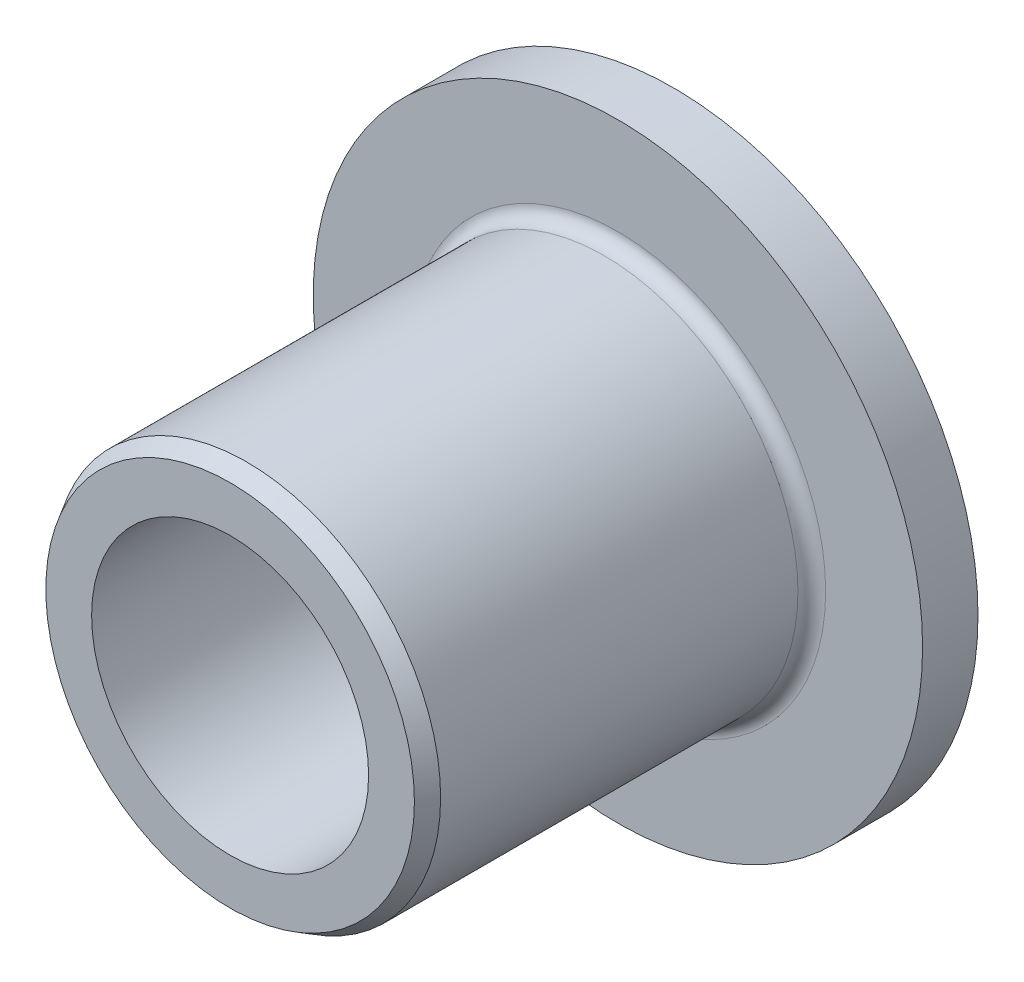
SolidWorks part; units mm, degrees
material "Igus T500"
ref_plane "Front Plane" through (0, 0, 0) normal (0, 0, 1) x (1, 0, 0)
ref_plane "Top Plane" through (0, 0, 0) normal (0, 1, 0) x (1, 0, 0)
ref_plane "Right Plane" through (0, 0, 0) normal (1, 0, 0) x (0, 0, -1)
ref_plane "Plane1" through (0, 0, 0) normal (0, 1, 0) x (-1, 0, 0)
sketch "Sketch1" plane through (0, 0, 0) normal (0, 1, 0) x (-1, 0, 0)
  line L0 (-3.5, 1) -> (-5.5, 1)
  line L1 (-5.5, 0) -> (-2.5, 0)
  line L2 (-2.5, 0) -> (-2.5, 8)
  line L3 (-3.3268, 8) -> (-3.5, 7.7)
  line L4 (-3.5, 7.7) -> (-3.5, 1)
  line L5 (0, 0) -> (0, 9.5) construction
  line L6 (-2.5, 8) -> (-3.3268, 8)
  line L8 (-5.5, 1) -> (-5.5, 0)
  dimension "D8" = 0.3
  dimension "d3" = 11
  dimension "b2" = 1
  dimension "D7" = 30
  dimension "b1" = 8
  dimension "d1" = 5
  dimension "d2" = 7
revolve "Revolve1" add sketch "Sketch1" angle 360 about L5
fillet "Fillet1" radius 0.25 1 edges at (3.5, 0, 1)
